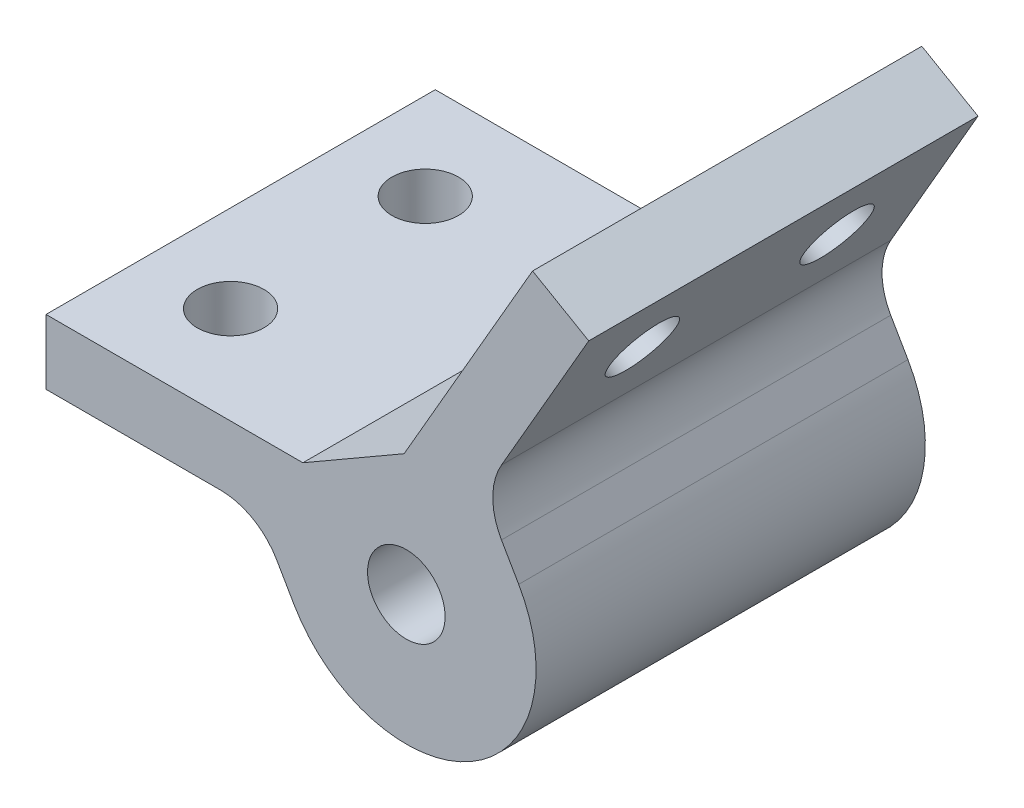
SolidWorks part; units mm, degrees
material "Custom Plastic"
ref_plane "Front Plane" through (0, 0, 0) normal (0, 0, 1) x (1, 0, 0)
ref_plane "Top Plane" through (0, 0, 0) normal (0, 1, 0) x (1, 0, 0)
ref_plane "Right Plane" through (0, 0, 0) normal (1, 0, 0) x (0, 0, -1)
sketch "Sketch1" plane through (0, 0, 0) normal (0, 0, 1) x (1, 0, 0)
  line L0 (0, 0) -> (-3.5195, 0) construction
  line L1 (-3.5195, 0) -> (-1.7598, 3.048) construction
  line L2 (-1.7598, 3.048) -> (1.7598, 3.048) construction
  line L3 (1.7598, 3.048) -> (0, 0) construction
  line L4 (-0.1088, 5.9076) -> (6.1777, 16.7962)
  line L5 (-5.0618, 3.048) -> (-17.6348, 3.048)
  line L6 (-17.6348, 3.048) -> (-17.6348, -0.127)
  line L7 (6.1777, 16.7962) -> (8.9274, 15.2087)
  line L8 (-5.4993, -3.175) -> (-7.259, -0.127)
  line L9 (5.4993, 3.175) -> (3.7395, 6.223)
  line L10 (0, 0) -> (-1.7598, 3.048) construction
  line L11 (-17.6348, -0.127) -> (-7.259, -0.127)
  line L12 (8.9274, 15.2087) -> (3.7395, 6.223)
  line L13 (-0.1088, 5.9076) -> (-5.0618, 3.048)
  line L14 (-0.1088, 5.9076) -> (-1.7598, 3.048) construction
  line L15 (-1.7598, 3.048) -> (-5.0618, 3.048) construction
  arc A0 (-5.4993, -3.175) -> (5.4993, 3.175) centre (0, 0) ccw
  dimension "D8" = 12.7
  dimension "D1" = 120
  dimension "D2" = 3.048
  dimension "D3" = 3.048
  dimension "D4" = 15.875
  dimension "D5" = 15.875
  dimension "D6" = 3.175
  dimension "D7" = 3.175
  dimension "D9" = 3.302
  dimension "D10" = 3.302
extrude "Boss-Extrude1" add sketch "Sketch1" along normal blind 19.05
hole_wizard "#6 Clearance Hole1" positions "3DSketch2" profile "Sketch4" hole size "#6" standard "ANSI Inch" end condition through all
sketch3d "3DSketch2"
  point P0 (0, 0, 0)
sketch "Sketch4" plane through (0, 0, 0) normal (1, 0, 0) x (0, 1, 0)
  line L0 (0, 0) -> (0, 19.05)
  line L1 (0, 19.05) -> (1.8986, 19.05)
  line L2 (1.8986, 19.05) -> (1.8986, 0)
  line L5 (1.8986, 0) -> (0, 0)
  line L11 (0, -6.35) -> (0, 107.95) construction
  dimension "Thru Hole Dia." = 3.7973
  dimension "Thru Hole Depth" = 19.05
fillet "Fillet1" radius 3.175 2 edges at (-7.259, -0.127, 9.525) (3.7395, 6.223, 9.525)
hole_wizard "E (0.25) Diameter Hole1" positions "Sketch7" profile "Sketch8" hole size "E" standard "ANSI Inch" end condition through all
sketch "Sketch7" plane through (0.11, -0.0635, 0) normal (0.866, -0.5, 0) x (0, 0, -1)
  line L0 (-19.05, 13.3634) -> (0, 13.3634) construction
  line L1 (-19.05, 9.0921) -> (-19.05, 17.6348) construction
  line L2 (0, 9.0921) -> (0, 17.6348) construction
  line L8 (-9.525, 17.6348) -> (-9.525, 9.0921) construction
  line L9 (-19.05, 17.6348) -> (0, 17.6348) construction
  line L10 (-19.05, 9.0921) -> (0, 9.0921) construction
  point P19 (-14.2875, 13.3634)
  point P21 (-4.7625, 13.3634)
  dimension "D1" = 9.525
sketch "Sketch8" plane through (6.7917, 11.5096, 4.7625) normal (0, 0, 1) x (0.5, 0.866, 0)
  line L0 (0, 0) -> (0, 23.7972)
  line L1 (0, 23.7972) -> (1.6319, 23.7972)
  line L2 (1.6319, 23.7972) -> (1.6319, 0)
  line L5 (1.6319, 0) -> (0, 0)
  line L11 (0, -6.35) -> (0, 107.95) construction
  dimension "Thru Hole Dia." = 3.2639
  dimension "Thru Hole Depth" = 23.7972
hole_wizard "E (0.25) Diameter Hole2" positions "3DSketch3" profile "Sketch9" hole size "E" standard "ANSI Inch" end condition through all
sketch3d "3DSketch3"
  line L0 (-13.3634, -0.127, 0) -> (-13.3634, -0.127, 19.05) construction
  line L1 (-17.6348, -0.127, 0) -> (-9.0921, -0.127, 0) construction
  line L2 (-17.6348, -0.127, 19.05) -> (-9.0921, -0.127, 19.05) construction
  line L7 (-17.6348, -0.127, 9.525) -> (-9.0921, -0.127, 9.525) construction
  line L8 (-17.6348, -0.127, 19.05) -> (-17.6348, -0.127, 0) construction
  line L9 (-9.0921, -0.127, 0) -> (-9.0921, -0.127, 19.05) construction
  point P17 (-13.3634, -0.127, 4.7625)
  point P19 (-13.3634, -0.127, 14.2875)
  dimension "D1" = 9.525
sketch "Sketch9" plane through (-13.3634, -0.127, 14.2875) normal (1, 0, 0) x (0, 0, -1)
  line L0 (0, 0) -> (0, 16.9232)
  line L1 (0, 16.9232) -> (1.6319, 16.9232)
  line L2 (1.6319, 16.9232) -> (1.6319, 0)
  line L5 (1.6319, 0) -> (0, 0)
  line L11 (0, -6.35) -> (0, 107.95) construction
  dimension "Thru Hole Dia." = 3.2639
  dimension "Thru Hole Depth" = 16.9232
equation "\"D5@Sketch1\"=\"D4@Sketch1\""
equation "\"D7@Sketch1\"=\"D6@Sketch1\""
equation "\"D2@Sketch1\"=\"D3@Sketch1\""
equation "\"D1@3DSketch3\"=\"D1@Sketch7\""
equation "\"D10@Sketch1\"=\"D9@Sketch1\""
